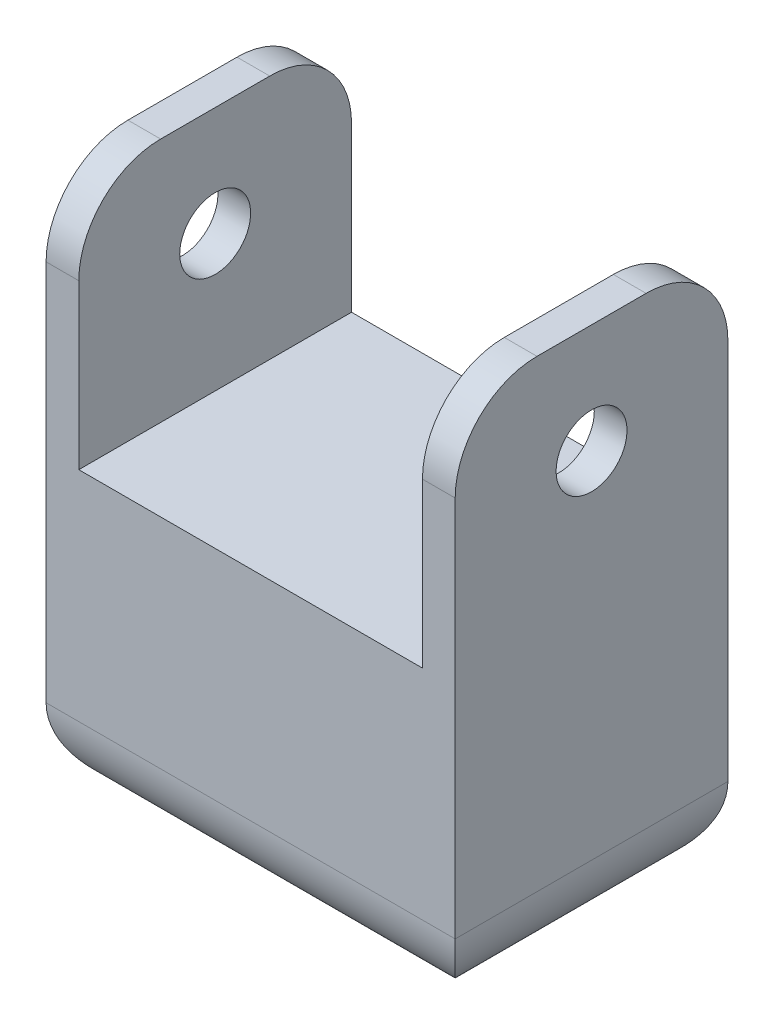
SolidWorks part; units mm, degrees
ref_plane "Front Plane" through (0, 0, 0) normal (0, 0, 1) x (1, 0, 0)
ref_plane "Top Plane" through (0, 0, 0) normal (0, 1, 0) x (1, 0, 0)
ref_plane "Right Plane" through (0, 0, 0) normal (1, 0, 0) x (0, 0, -1)
sketch "Sketch1" plane through (0, 0, 0) normal (0, 1, 0) x (1, 0, 0)
  line L1 (-19.05, 12.7) -> (19.05, 12.7)
  line L2 (-19.05, 12.7) -> (-19.05, -12.7)
  line L3 (-19.05, -12.7) -> (19.05, -12.7)
  line L4 (19.05, 12.7) -> (19.05, -12.7)
  line L5 (-19.05, 12.7) -> (19.05, -12.7) construction
  line L6 (-19.05, -12.7) -> (19.05, 12.7) construction
  point P0 (0, 0)
  dimension "D1" = 38.1
  dimension "D2" = 25.4
extrude "Boss-Extrude1" add sketch "Sketch1" along normal blind 25.4
sketch "Sketch2" plane through (0, 25.4, 0) normal (0, 1, 0) x (1, 0, 0)
  line L0 (19.05, 12.7) -> (-19.05, 12.7) construction
  line L1 (-16.002, 12.7) -> (16.002, 12.7)
  line L2 (-16.002, 12.7) -> (-16.002, -12.7)
  line L3 (-16.002, -12.7) -> (16.002, -12.7)
  line L4 (16.002, 12.7) -> (16.002, -12.7)
  line L5 (-19.05, -12.7) -> (19.05, -12.7) construction
  dimension "D1" = 32.004
  dimension "D2" = 16.002
extrude "Cut-Extrude1" cut sketch "Sketch2" against normal blind 22.86
sketch "Sketch3" plane through (-19.05, 0, 0) normal (-1, 0, 0) x (0, 0, 1)
  line L0 (-12.7, 0) -> (12.7, 0) construction
  circle A0 centre (0, 15.24) radius 3.302
  point P4 (0, 15.24)
  dimension "D1" = 6.604
  dimension "D2" = 15.24
extrude "Cut-Extrude2" cut sketch "Sketch3" against normal through all
fillet "Fillet1" radius 7.62 4 edges at (17.526, 25.4, 12.7) (17.526, 25.4, -12.7) (-17.526, 25.4, 12.7) (-17.526, 25.4, -12.7)
sketch "Sketch4" plane through (0, 0, 0) normal (0, -1, 0) x (1, 0, 0)
  line L1 (-19.05, 12.7) -> (19.05, 12.7)
  line L2 (-19.05, 12.7) -> (-19.05, -12.7)
  line L3 (-19.05, -12.7) -> (19.05, -12.7)
  line L4 (19.05, 12.7) -> (19.05, -12.7)
extrude "Boss-Extrude2" add sketch "Sketch4" along normal blind 25.4
fillet "Fillet2" radius 7.62 4 edges at (0, -25.4, 12.7) (19.05, -25.4, 0) (0, -25.4, -12.7) (-19.05, -25.4, 0)
